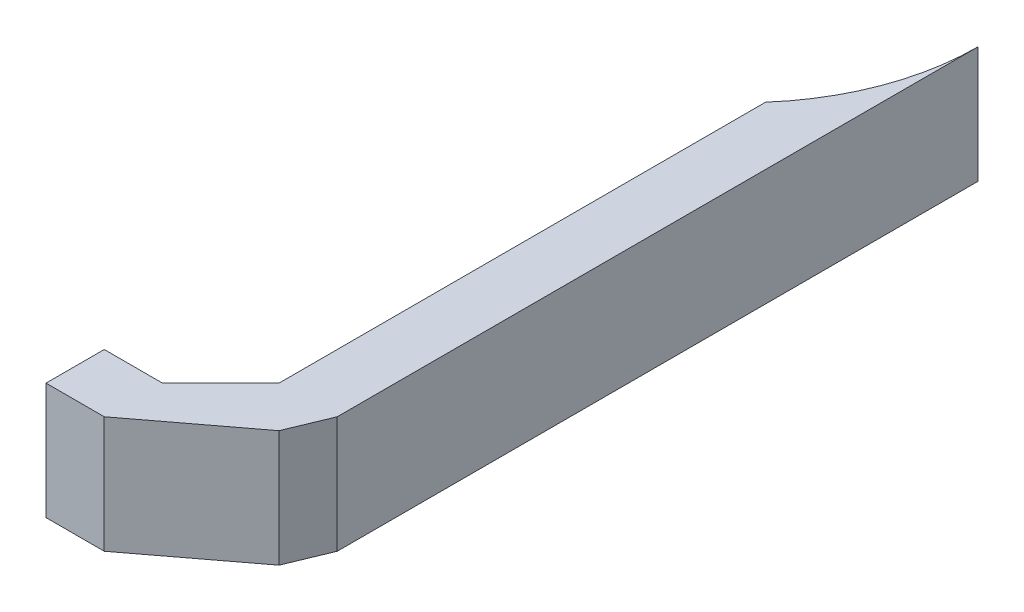
SolidWorks part; units mm, degrees
material "1060 Alloy"
ref_plane "Front Plane" through (0, 0, 0) normal (0, 0, 1) x (1, 0, 0)
ref_plane "Top Plane" through (0, 0, 0) normal (0, 1, 0) x (1, 0, 0)
ref_plane "Right Plane" through (0, 0, 0) normal (1, 0, 0) x (0, 0, -1)
sketch "Sketch1" plane through (0, 0, 0) normal (0, 1, 0) x (1, 0, 0)
  line L0 (0, 0) -> (5, 0)
  line L1 (0, 0) -> (0, 5)
  line L2 (0, 5) -> (5, 5)
  line L3 (5, 5) -> (10, 5) construction
  line L4 (10, 5) -> (10, 20) construction
  line L6 (10, 20) -> (10, 51.7712)
  line L7 (7.5, 7.5) -> (11.0355, 3.9645) construction
  line L11 (15, 10) -> (15, 65)
  line L12 (5, 5) -> (10, 10)
  line L13 (10, 10) -> (10, 20)
  line L14 (10, 70) -> (8.2288, 70) construction
  line L15 (10, 10) -> (13.5355, 6.4645) construction
  line L16 (0, 5) -> (-5, 5) construction
  line L17 (-5, 5) -> (-5, 40) construction
  line L18 (-5, 40) -> (-6.6296, 40) construction
  line L19 (-3.9838, 70) -> (-3.9838, 55) construction
  line L20 (5, 0) -> (13.5355, 6.4645)
  line L21 (-3.9838, 70) -> (-6.6296, 70) construction
  line L22 (13.5355, 6.4645) -> (15, 10)
  arc A0 (10, 51.7712) -> (15, 65) centre (-5, 65) ccw
extrude "Boss-Extrude1" add sketch "Sketch1" along normal blind 10
